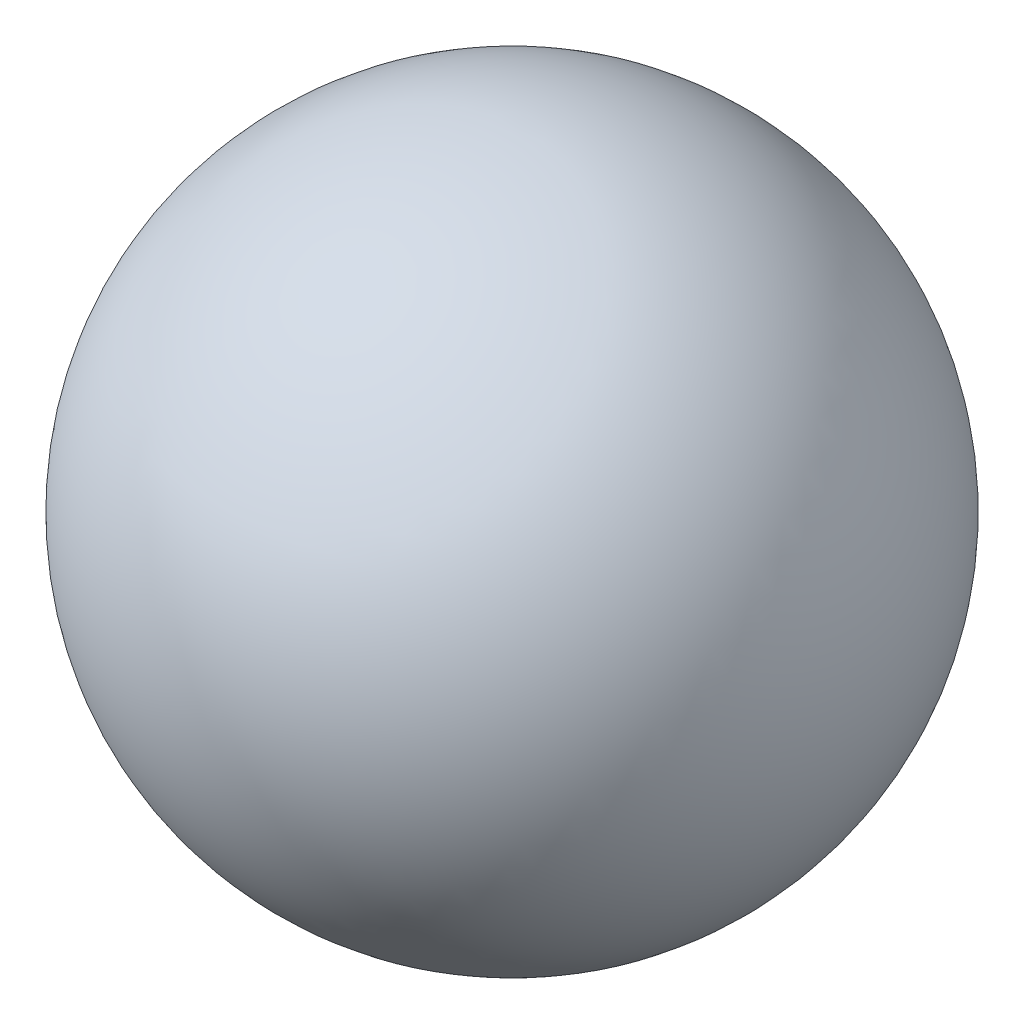
SolidWorks part; units mm, degrees
material "合金钢"
ref_plane "前视基准面" through (0, 0, 0) normal (0, 0, 1) x (1, 0, 0)
ref_plane "上视基准面" through (0, 0, 0) normal (0, 1, 0) x (1, 0, 0)
ref_plane "右视基准面" through (0, 0, 0) normal (1, 0, 0) x (0, 0, -1)
sketch "草图1" plane through (0, 0, 0) normal (0, 0, 1) x (1, 0, 0)
  line L0 (0, 59.062) -> (0, -51.3402) construction
  line L1 (58.75, 23.4563) -> (58.75, -23.4563) construction
  line L2 (58.75, 14) -> (58.75, -14)
  arc A0 (58.75, -14) -> (58.75, 14) centre (58.75, 0) ccw
  dimension "D1" = 58.75
  dimension "D2" = 28
revolve "旋转1" add sketch "草图1" angle 360 about L1
